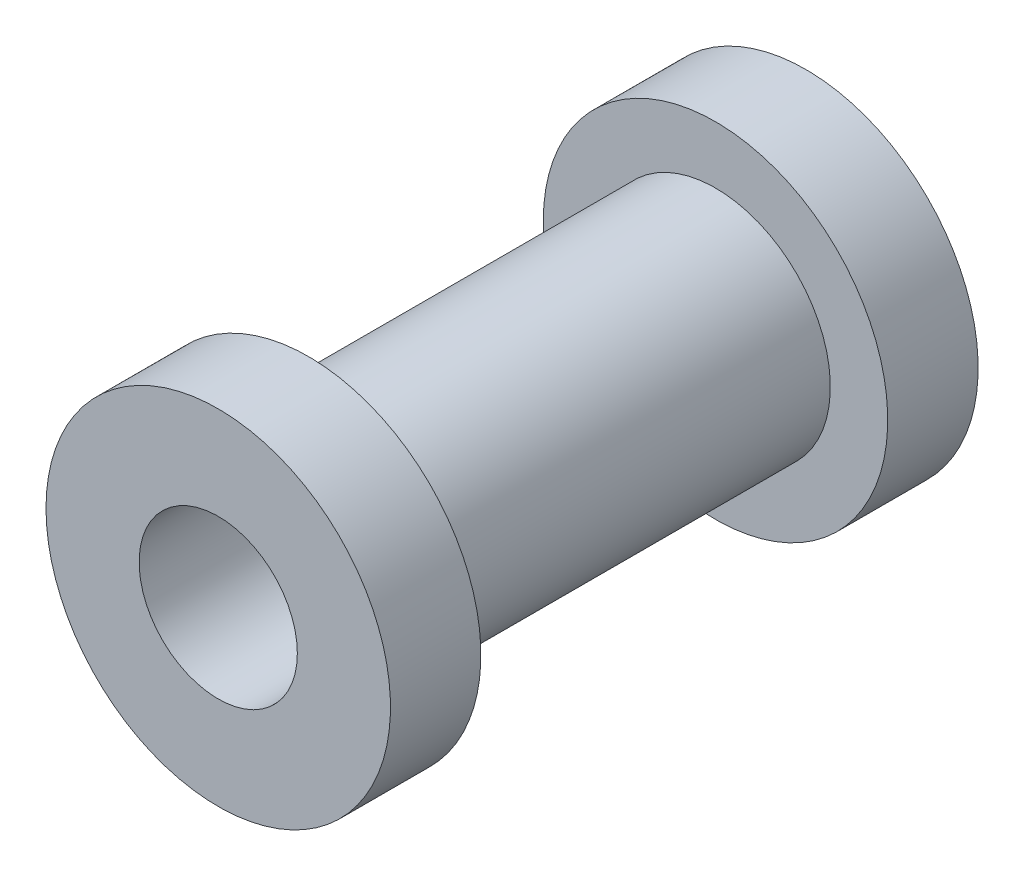
SolidWorks part; units mm, degrees
ref_plane "Front Plane" through (0, 0, 0) normal (0, 0, 1) x (1, 0, 0)
ref_plane "Top Plane" through (0, 0, 0) normal (0, 1, 0) x (1, 0, 0)
ref_plane "Right Plane" through (0, 0, 0) normal (1, 0, 0) x (0, 0, -1)
sketch "Sketch1" plane through (0, 0, 0) normal (0, 0, 1) x (1, 0, 0)
  circle A0 centre (0, 0) radius 17.5
  circle A1 centre (0, 0) radius 25.4
  dimension "D1" = 35
  dimension "D2" = 50.8
extrude "Boss-Extrude1" add sketch "Sketch1" along normal mid plane 130
sketch "Sketch2" plane through (0, 0, -65) normal (0, 0, -1) x (-1, 0, 0)
  circle A0 centre (0, 0) radius 38.1
  circle A1 centre (0, 0) radius 25.4 construction
  circle A2 centre (0, 0) radius 25.4
  dimension "D1" = 76.2
extrude "Boss-Extrude2" add sketch "Sketch2" against normal blind 20
mirror "Mirror1" about plane through (0, 0, 0) normal (0, 0, 1) of "Boss-Extrude2"
